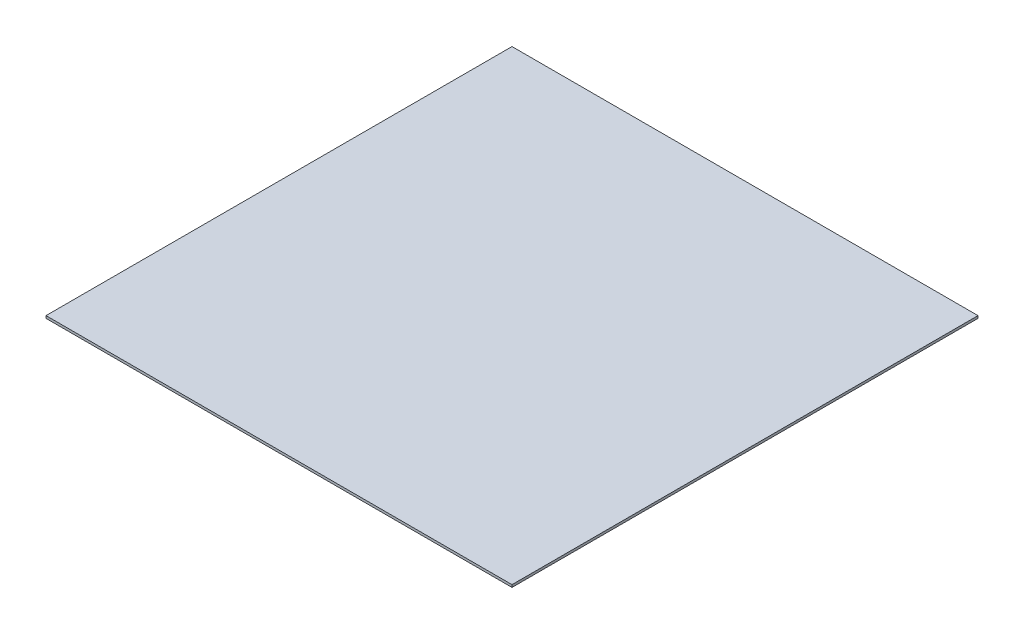
SolidWorks part; units mm, degrees
ref_plane "Front Plane" through (0, 0, 0) normal (0, 0, 1) x (1, 0, 0)
ref_plane "Top Plane" through (0, 0, 0) normal (0, 1, 0) x (1, 0, 0)
ref_plane "Right Plane" through (0, 0, 0) normal (1, 0, 0) x (0, 0, -1)
sketch "Sketch1" plane through (0, 0, 0) normal (0, 1, 0) x (1, 0, 0)
  line L1 (-304.8, 304.8) -> (304.8, 304.8)
  line L2 (-304.8, 304.8) -> (-304.8, -304.8)
  line L3 (-304.8, -304.8) -> (304.8, -304.8)
  line L4 (304.8, 304.8) -> (304.8, -304.8)
  line L5 (-304.8, 304.8) -> (304.8, -304.8) construction
  line L6 (-304.8, -304.8) -> (304.8, 304.8) construction
  point P0 (0, 0)
  dimension "D1" = 609.6
  dimension "D2" = 609.6
extrude "Boss-Extrude1" add sketch "Sketch1" along normal blind 3.175
